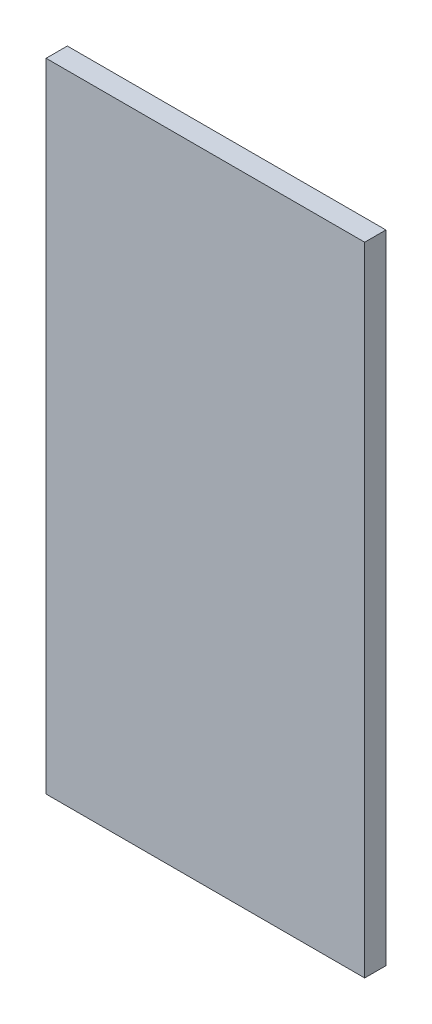
SolidWorks part; units mm, degrees
ref_plane "Alzado" through (0, 0, 0) normal (0, 0, 1) x (1, 0, 0)
ref_plane "Planta" through (0, 0, 0) normal (0, 1, 0) x (1, 0, 0)
ref_plane "Vista lateral" through (0, 0, 0) normal (1, 0, 0) x (0, 0, -1)
ref_plane "Plano1" through (0, 0, 360) normal (0, 0, -1) x (-1, 0, 0)
sketch "Croquis1" plane through (0, 0, 360) normal (0, 0, -1) x (-1, 0, 0)
  line L0 (7.7541, -147.1656) -> (7.7541, -132.1656) construction
  line L1 (-157.2459, -147.1656) -> (172.7541, -147.1656) construction
  line L2 (-157.2459, 182.8344) -> (172.7541, 182.8344) construction
  line L3 (7.7541, 167.8344) -> (7.7541, 182.8344) construction
  line L4 (-67.2459, 167.8344) -> (82.7541, 167.8344)
  line L5 (-67.2459, 167.8344) -> (-67.2459, -132.1656)
  line L6 (-67.2459, -132.1656) -> (82.7541, -132.1656)
  line L7 (82.7541, 167.8344) -> (82.7541, -132.1656)
  point P6 (7.7541, 12.1668)
  dimension "D1" = 150
  dimension "D2" = 300
extrude "Saliente-Extruir1" add sketch "Croquis1" along normal blind 10
